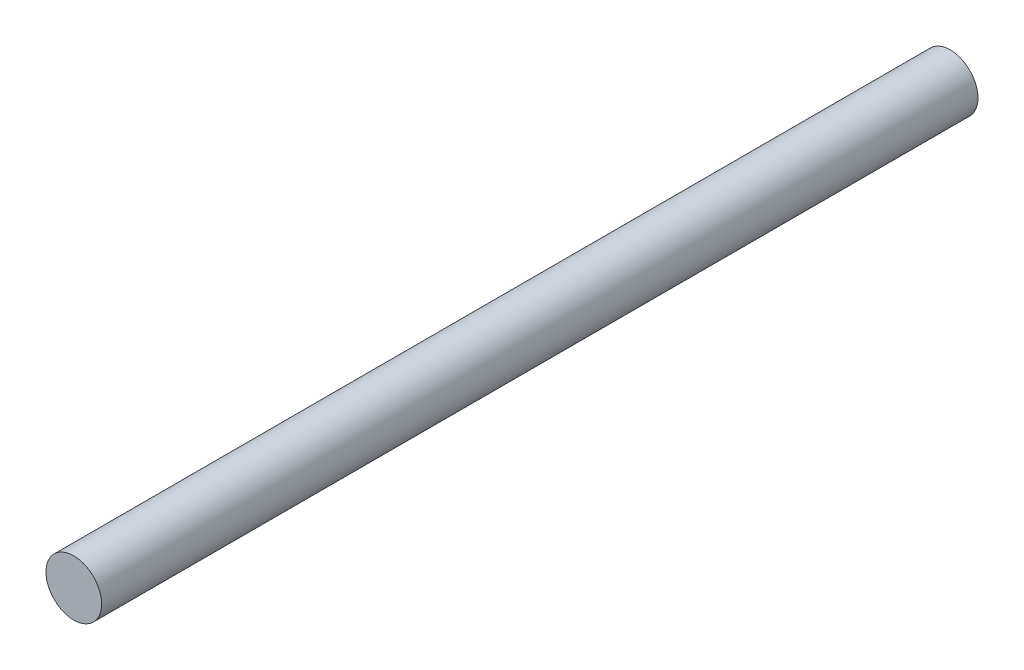
SolidWorks part; units mm, degrees
ref_plane "Front Plane" through (0, 0, 0) normal (0, 0, 1) x (1, 0, 0)
ref_plane "Top Plane" through (0, 0, 0) normal (0, 1, 0) x (1, 0, 0)
ref_plane "Right Plane" through (0, 0, 0) normal (1, 0, 0) x (0, 0, -1)
sketch "Sketch1" plane through (0, 0, 0) normal (0, 0, 1) x (1, 0, 0)
  circle A0 centre (125.6149, 32.8358) radius 9.525
extrude "Boss-Extrude1" add sketch "Sketch1" along normal blind 300 contours A0
